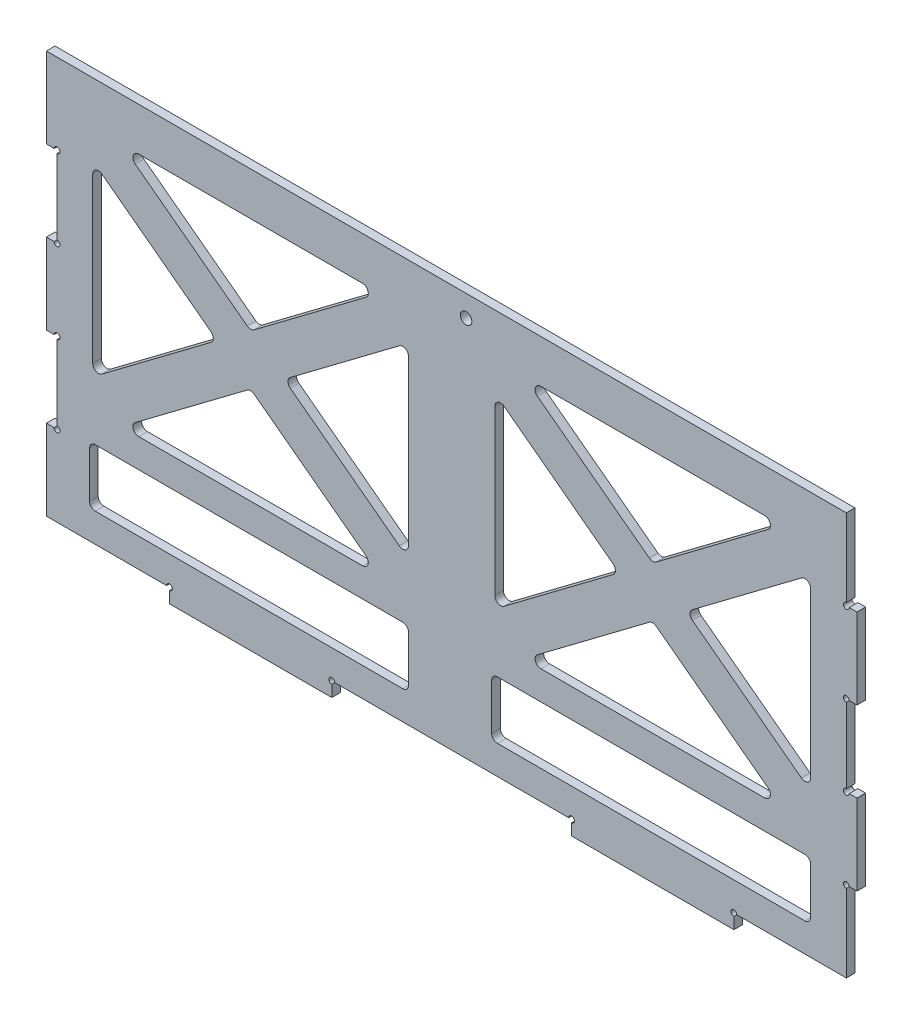
SolidWorks part; units mm, degrees
material "Alumina"
ref_plane "Front Plane" through (0, 0, 0) normal (0, 0, 1) x (1, 0, 0)
ref_plane "Top Plane" through (0, 0, 0) normal (0, 1, 0) x (1, 0, 0)
ref_plane "Right Plane" through (0, 0, 0) normal (1, 0, 0) x (0, 0, -1)
sketch "Sketch1" plane through (0, 0, 0) normal (0, 0, 1) x (1, 0, 0)
  line L1 (-140.85, -70) -> (140.85, -70)
  line L2 (-140.85, -70) -> (-140.85, 70)
  line L3 (-140.85, 70) -> (140.85, 70)
  line L4 (140.85, -70) -> (140.85, 70)
  line L5 (-140.85, -70) -> (140.85, 70) construction
  line L6 (-140.85, 70) -> (140.85, -70) construction
  point P0 (0, 0)
extrude "Boss-Extrude1" add sketch "Sketch1" along normal blind 3
sketch "Sketch2" plane through (0, 0, 3) normal (0, 0, 1) x (1, 0, 0)
  line L1 (-140.85, 70) -> (-140.85, -70) construction
  line L2 (-125.85, -60) -> (-15, -60)
  line L3 (-125.85, -60) -> (-125.85, -40)
  line L4 (-125.85, -40) -> (-15, -40)
  line L6 (-15, -60) -> (-15, -40)
  line L7 (-125.85, -60) -> (-15, -40) construction
  line L8 (-125.85, -40) -> (-15, -60) construction
  line L9 (-140.85, -70) -> (140.85, -70) construction
  line L10 (140.85, 70) -> (-140.85, 70) construction
  line L11 (-124.75, -30) -> (-15, -30)
  line L12 (-124.75, -30) -> (-124.75, 55)
  line L13 (-124.75, 55) -> (-15, 55)
  line L14 (-15, -30) -> (-15, 55)
  line L15 (-124.75, -30) -> (-15, 55) construction
  line L16 (-124.75, 55) -> (-15, -30) construction
  line L17 (-124.75, 45) -> (-25, -30)
  line L18 (-114.75, 55) -> (-15, -20)
  line L19 (-15, 45) -> (-114.75, -30)
  line L20 (-25, 55) -> (-124.75, -20)
  line L21 (13.9, -60) -> (124.75, -60)
  line L22 (13.9, -60) -> (13.9, -40)
  line L23 (13.9, -40) -> (124.75, -40)
  line L24 (124.75, -60) -> (124.75, -40)
  line L25 (15, -30) -> (124.75, -30)
  line L26 (15, -30) -> (15, 55)
  line L27 (15, 55) -> (124.75, 55)
  line L28 (124.75, -30) -> (124.75, 55)
  line L29 (15, 45) -> (114.75, -30)
  line L30 (25, 55) -> (124.75, -20)
  line L31 (124.75, 45) -> (25, -30)
  line L32 (114.75, 55) -> (15, -20)
  line L33 (13.9, -60) -> (124.75, -40) construction
  line L34 (13.9, -40) -> (124.75, -60) construction
  line L35 (15, -30) -> (124.75, 55) construction
  line L36 (15, 55) -> (124.75, -30) construction
  point P0 (-70.425, -50)
  point P9 (-69.875, 12.5)
  point P25 (69.325, -50)
  point P30 (69.875, 12.5)
  dimension "D1" = 15
  dimension "D2" = 10
  dimension "D3" = 15
  dimension "D4" = 10
  dimension "D5" = 10
  dimension "D6" = 10
  dimension "D7" = 10
  dimension "D8" = 10
extrude "Cut-Extrude1" cut sketch "Sketch2" against normal through all contours L20 L17 L12 | L20 L13 L18 | L14 L19 L18 | L17 L19 L11 | L2 L6 L4 L3 | L21 L24 L23 L22 | L29 L31 L25 | L32 L29 L26 | L32 L27 L30 | L28 L31 L30
fillet "Fillet1" radius 2 30 edges at (-15, 45, 1.5) (-81.525, 12.5, 1.5) (-25, -30, 1.5) (25, -30, 1.5) (-15, -20, 1.5) (124.75, -20, 1.5) (-15, -60, 1.5) (-15, -40, 1.5) (-25, 55, 1.5) (114.75, 55, 1.5) (124.75, 45, 1.5) (124.75, -40, 1.5) (114.75, -30, 1.5) (124.75, -60, 1.5) (13.9, -60, 1.5) (15, -20, 1.5) (69.875, 3.7406, 1.5) (15, 45, 1.5) (13.9, -40, 1.5) (81.525, 12.5, 1.5) (25, 55, 1.5) (-58.225, 12.5, 1.5) (-114.75, 55, 1.5) (-69.875, 3.7406, 1.5) (-124.75, 45, 1.5) (-124.75, -20, 1.5) (-69.875, 21.2594, 1.5) (-114.75, -30, 1.5) (-125.85, -60, 1.5) (-125.85, -40, 1.5)
sketch "Sketch3" plane through (0, 0, 3) normal (0, 0, 1) x (1, 0, 0)
  line L0 (140.85, -70) -> (140.85, 70) construction
  line L1 (140.85, 70) -> (137.15, 70)
  line L2 (140.85, 70) -> (140.85, 42)
  line L3 (140.85, 42) -> (137.15, 42)
  line L4 (137.15, 70) -> (137.15, 42)
  line L5 (140.85, -70) -> (137.15, -70)
  line L6 (140.85, -70) -> (140.85, -42)
  line L7 (140.85, -42) -> (137.15, -42)
  line L8 (137.15, -70) -> (137.15, -42)
  line L9 (140.85, -14) -> (137.15, -14)
  line L10 (140.85, -14) -> (140.85, 14)
  line L11 (140.85, 14) -> (137.15, 14)
  line L12 (137.15, -14) -> (137.15, 14)
  line L13 (-140.85, 70) -> (-140.85, -70) construction
  line L14 (-140.85, -42) -> (-137.15, -42)
  line L15 (-140.85, -42) -> (-140.85, -14)
  line L16 (-140.85, -14) -> (-137.15, -14)
  line L17 (-137.15, -42) -> (-137.15, -14)
  line L19 (-137.15, 42) -> (-140.85, 42)
  line L20 (-137.15, 42) -> (-137.15, 14)
  line L21 (-137.15, 14) -> (-140.85, 14)
  line L22 (-140.85, 42) -> (-140.85, 14)
  dimension "D1" = 28
extrude "Cut-Extrude2" cut sketch "Sketch3" against normal through all
sketch "Sketch4" plane through (0, 0, 3) normal (0, 0, 1) x (1, 0, 0)
  line L1 (-140.85, -70) -> (137.15, -70) construction
  line L2 (-98.075, -75) -> (-41.675, -75)
  line L3 (-98.075, -75) -> (-98.075, -70)
  line L4 (-98.075, -70) -> (-41.675, -70)
  line L5 (-41.675, -75) -> (-41.675, -70)
  line L6 (-98.075, -75) -> (-41.675, -70) construction
  line L7 (-98.075, -70) -> (-41.675, -75) construction
  line L9 (41.675, -75) -> (98.075, -75)
  line L10 (41.675, -75) -> (41.675, -70)
  line L11 (41.675, -70) -> (98.075, -70)
  line L12 (98.075, -75) -> (98.075, -70)
  line L13 (41.675, -75) -> (98.075, -70) construction
  line L14 (41.675, -70) -> (98.075, -75) construction
  point P5 (69.875, -72.5)
  point P8 (-69.875, -72.5)
extrude "Boss-Extrude2" add sketch "Sketch4" against normal blind 3
fillet "Fillet2" radius 2 2 edges at (58.225, 12.5, 1.5) (69.875, 21.2594, 1.5)
sketch "Sketch5" plane through (0, 0, 0) normal (0, 0, -1) x (-1, 0, 0)
  circle A0 centre (-5, 62.5) radius 2
extrude "Cut-Extrude3" cut sketch "Sketch5" against normal through all
sketch "Sketch6" plane through (0, 0, 3) normal (0, 0, 1) x (1, 0, 0)
  circle A0 centre (-137.15, 42) radius 1
  circle A1 centre (-137.15, 14) radius 1
  circle A2 centre (-137.15, -14) radius 1
  circle A3 centre (-137.15, -42) radius 1
  circle A4 centre (-98.075, -70) radius 1
  circle A5 centre (-41.675, -70) radius 1
  circle A6 centre (41.675, -70) radius 1
  circle A7 centre (98.075, -70) radius 1
  circle A8 centre (137.15, -42) radius 1
  circle A9 centre (137.15, -14) radius 1
  circle A10 centre (137.15, 14) radius 1
  circle A11 centre (137.15, 42) radius 1
extrude "Cut-Extrude4" cut sketch "Sketch6" against normal through all
